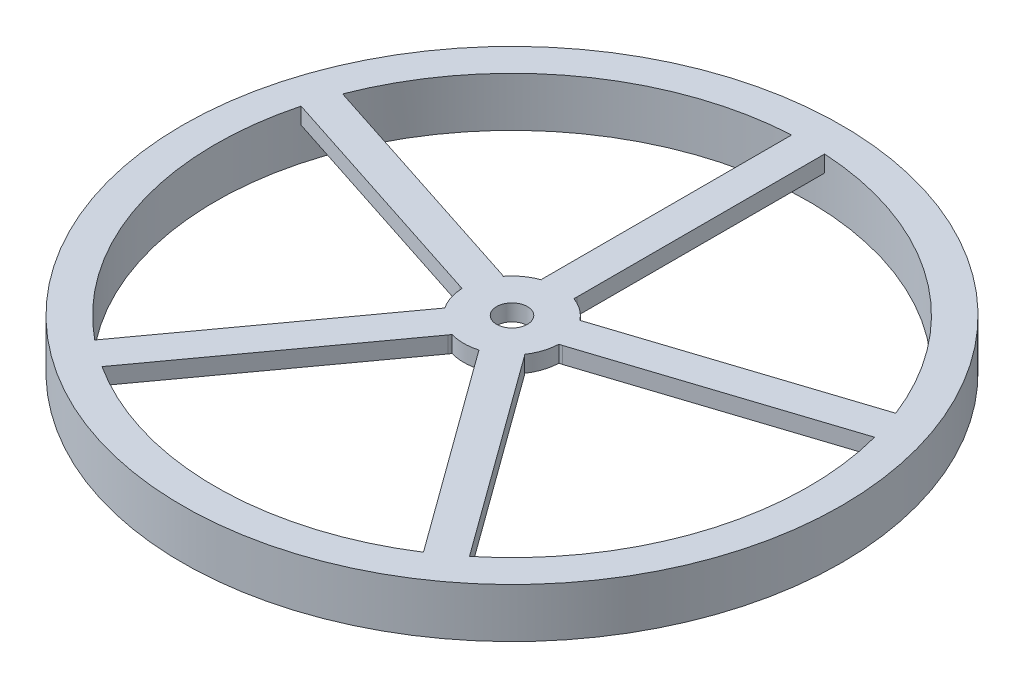
SolidWorks part; units mm, degrees
ref_plane "Front Plane" through (0, 0, 0) normal (0, 0, 1) x (1, 0, 0)
ref_plane "Top Plane" through (0, 0, 0) normal (0, 1, 0) x (1, 0, 0)
ref_plane "Right Plane" through (0, 0, 0) normal (1, 0, 0) x (0, 0, -1)
sketch "Sketch1" plane through (0, 0, 0) normal (0, 1, 0) x (1, 0, 0)
  circle A0 centre (0, 0) radius 180
  dimension "D1" = 360
extrude "Extrude-Thin1" add sketch "Sketch1" along normal blind 30 thin
sketch "Sketch2" plane through (0, 30, 0) normal (0, 1, 0) x (1, 0, 0)
  circle A0 centre (0, 0) radius 9.35
  dimension "D1" = 18.7
extrude "Extrude-Thin2" add sketch "Sketch2" against normal blind 10 separate body thin
sketch "Sketch3" plane through (0, 30, 0) normal (0, 1, 0) x (1, 0, 0)
  line L0 (0, 29.35) -> (0, 180) construction
  line L1 (10, 29.35) -> (10, 180)
  line L2 (-10, 29.35) -> (-10, 180)
  circle A0 centre (0, 0) radius 29.35 construction
  circle A1 centre (0, 0) radius 180 construction
  arc A2 (10, 29.35) -> (-10, 29.35) centre (0, 29.35) cw
  arc A3 (10, 180) -> (-10, 180) centre (0, 180) ccw
  dimension "D1" = 10
  dimension "D2" = 10
extrude "Boss-Extrude1" add sketch "Sketch3" against normal blind 10
pattern_circular "CirPattern1" count 5 over 360 about axis through (0, 0, 0) along (0, 1, 0) of "Boss-Extrude1"
scale "Scale3" scale about centroid uniform scaling yes scale factor 0.75
